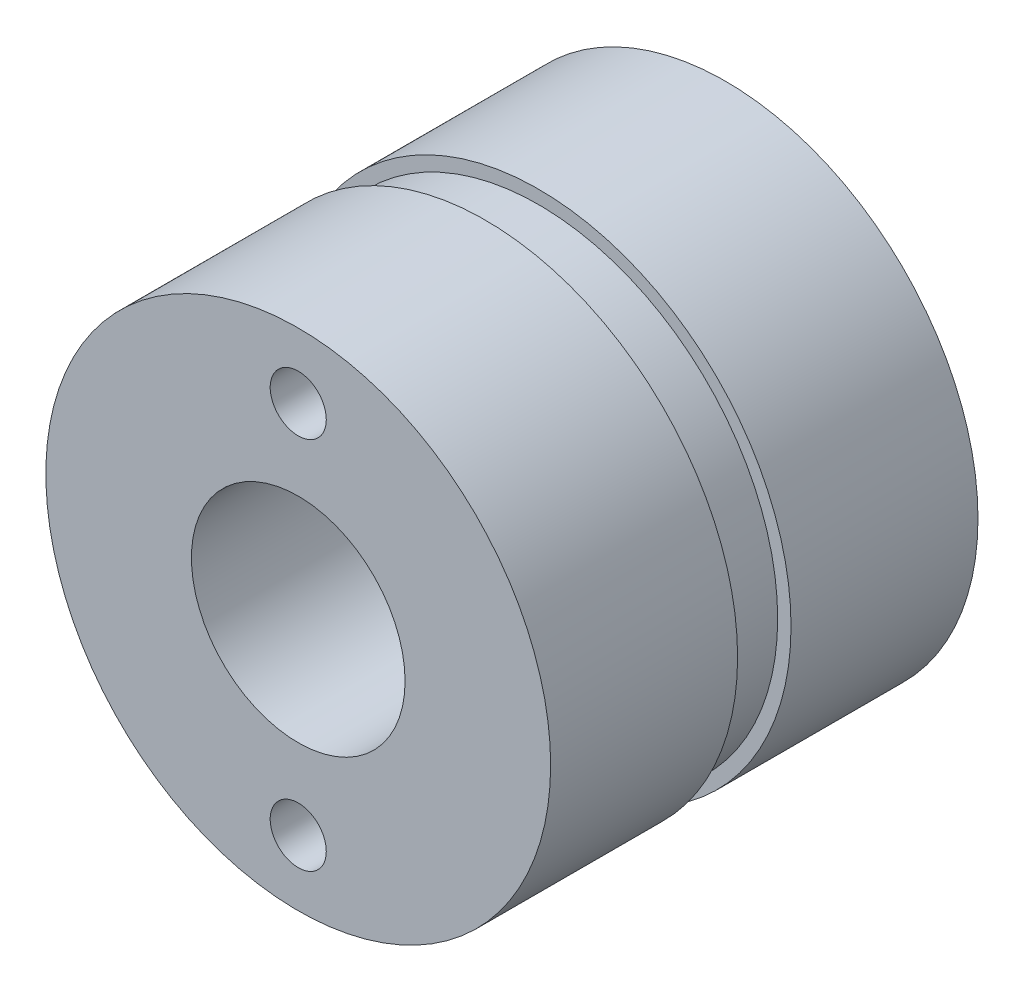
SolidWorks part; units mm, degrees
ref_plane "Front Plane" through (0, 0, 0) normal (0, 0, 1) x (1, 0, 0)
ref_plane "Top Plane" through (0, 0, 0) normal (0, 1, 0) x (1, 0, 0)
ref_plane "Right Plane" through (0, 0, 0) normal (1, 0, 0) x (0, 0, -1)
sketch "Sketch1" plane through (0, 0, 0) normal (0, 0, 1) x (1, 0, 0)
  circle A0 centre (0, 0) radius 9.45
extrude "Boss-Extrude1" add sketch "Sketch1" along normal blind 7 contours A0
sketch "Sketch2" plane through (0, 0, 7) normal (0, 0, 1) x (1, 0, 0)
  circle A0 centre (0, 0) radius 8.95
extrude "Boss-Extrude2" add sketch "Sketch2" along normal blind 2
sketch "Sketch3" plane through (0, 0, 9) normal (0, 0, 1) x (1, 0, 0)
  circle A0 centre (0, 0) radius 9.45
extrude "Boss-Extrude3" add sketch "Sketch3" along normal blind 7
sketch "Sketch4" plane through (0, 0, 16) normal (0, 0, 1) x (1, 0, 0)
  circle A0 centre (0, 0) radius 4
extrude "Cut-Extrude1" cut sketch "Sketch4" against normal through all
sketch "Sketch5" plane through (0, 0, 16) normal (0, 0, 1) x (1, 0, 0)
  point P0 (0, -7)
  point P2 (0, 7)
hole_wizard "M2.5x0.45 Tapped Hole1" positions "Sketch5" profile "Sketch6" tap size "M2.5x0.45" standard "JIS"
cosmetic thread "Hole Thread1" parameters "D1"=4, "D2"=2.5
cosmetic thread "Hole Thread2" parameters "D1"=4, "D2"=2.5
sketch "Sketch6" plane through (0, -7, 16) normal (1, 0, 0) x (0, -1, 0)
  line L0 (0, 0) -> (0, 7.6309)
  line L1 (0, 7.6309) -> (1.05, 7)
  line L2 (1.05, 7) -> (1.05, 0)
  line L5 (1.05, 0) -> (0, 0)
  line L10 (0, 7.6309) -> (-1.05, 7) construction
  line L11 (0, -6.35) -> (0, 107.95) construction
  dimension "Tap Drill Dia." = 2.1
  dimension "Tap Drill Depth" = 7
  dimension "Drill Angle" = 118
sketch "Sketch7" plane through (0, 0, 0) normal (0, 0, -1) x (-1, 0, 0)
  point P0 (0, 7)
  point P2 (0, -7)
hole_wizard "M2.5x0.45 Tapped Hole2" positions "Sketch7" profile "Sketch8" tap size "M2.5x0.45" standard "JIS"
sketch "Sketch8" plane through (0, 7, 0) normal (1, 0, 0) x (0, 1, 0)
  line L0 (0, 0) -> (0, 7.6309)
  line L1 (0, 7.6309) -> (1.05, 7)
  line L2 (1.05, 7) -> (1.05, 0)
  line L5 (1.05, 0) -> (0, 0)
  line L10 (0, 7.6309) -> (-1.05, 7) construction
  line L11 (0, -6.35) -> (0, 107.95) construction
  dimension "Tap Drill Dia." = 2.1
  dimension "Tap Drill Depth" = 7
  dimension "Drill Angle" = 118
cosmetic thread "Hole Thread3" parameters "D1"=4, "D2"=2.5
cosmetic thread "Hole Thread4" parameters "D1"=4, "D2"=2.5
